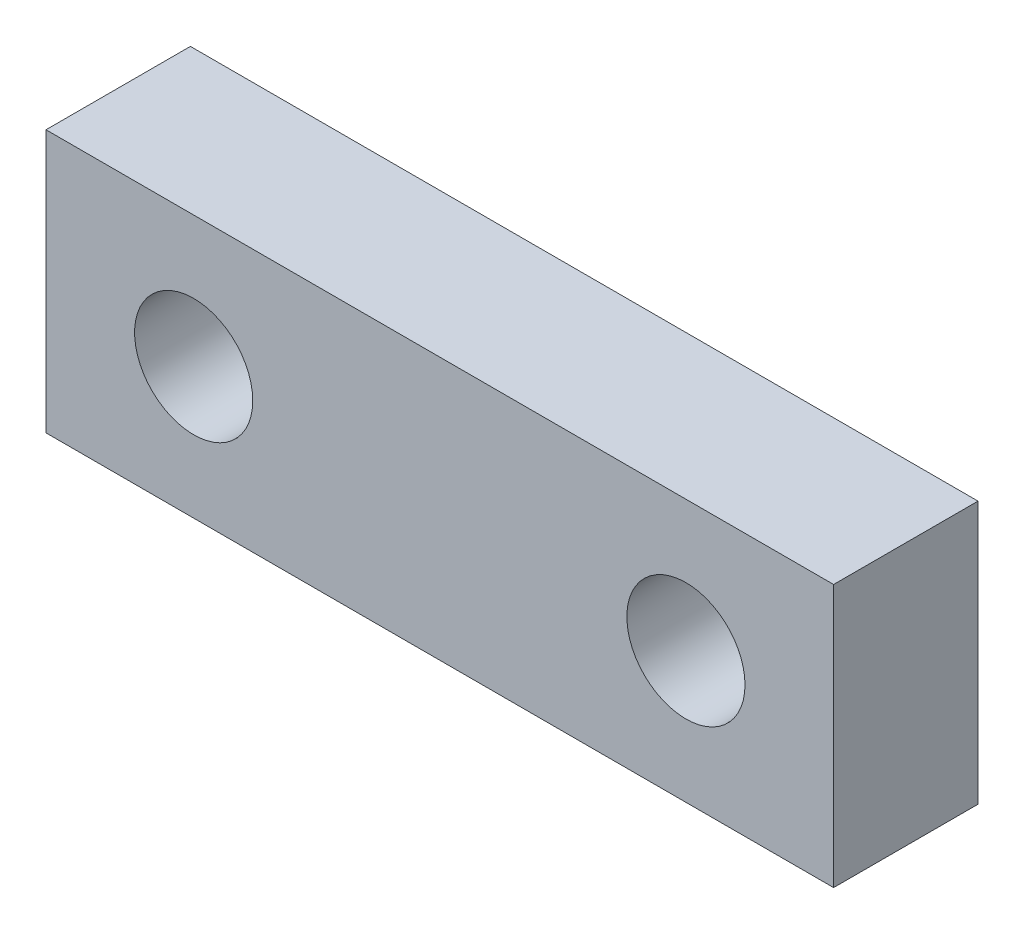
SolidWorks part; units mm, degrees
ref_plane "Front Plane" through (0, 0, 0) normal (0, 0, 1) x (1, 0, 0)
ref_plane "Top Plane" through (0, 0, 0) normal (0, 1, 0) x (1, 0, 0)
ref_plane "Right Plane" through (0, 0, 0) normal (1, 0, 0) x (0, 0, -1)
sketch "Sketch1" plane through (0, 0, 0) normal (0, 0, 1) x (1, 0, 0)
  line L0 (-9.375, 0) -> (9.375, 0) construction
  line L2 (15, 5) -> (-15, 5)
  line L3 (15, 5) -> (15, -5)
  line L4 (15, -5) -> (-15, -5)
  line L5 (-15, 5) -> (-15, -5)
  line L6 (15, 5) -> (-15, -5) construction
  line L7 (15, -5) -> (-15, 5) construction
  circle A0 centre (-9.375, 0) radius 3.5
  circle A1 centre (9.375, 0) radius 3.5
  point P4 (0, 0)
  dimension "D1" = 18.75
  dimension "D2" = 9.375
  dimension "D3" = 7
  dimension "D4" = 7
  dimension "D5" = 30
  dimension "D6" = 10
extrude "Boss-Extrude1" add sketch "Sketch1" along normal blind 1.5
sketch "Sketch2" plane through (0, 0, 1.5) normal (0, 0, 1) x (1, 0, 0)
  line L1 (15, -5) -> (-15, -5)
  line L2 (15, -5) -> (15, 5)
  line L3 (15, 5) -> (-15, 5)
  line L4 (-15, -5) -> (-15, 5)
  line L5 (15, -5) -> (-15, 5) construction
  line L6 (15, 5) -> (-15, -5) construction
  circle A0 centre (-9.375, 0) radius 2.25
  circle A1 centre (9.375, 0) radius 2.25
  point P0 (0, 0)
  dimension "D1" = 4.5
  dimension "D2" = 4.5
extrude "Boss-Extrude2" add sketch "Sketch2" along normal blind 4
